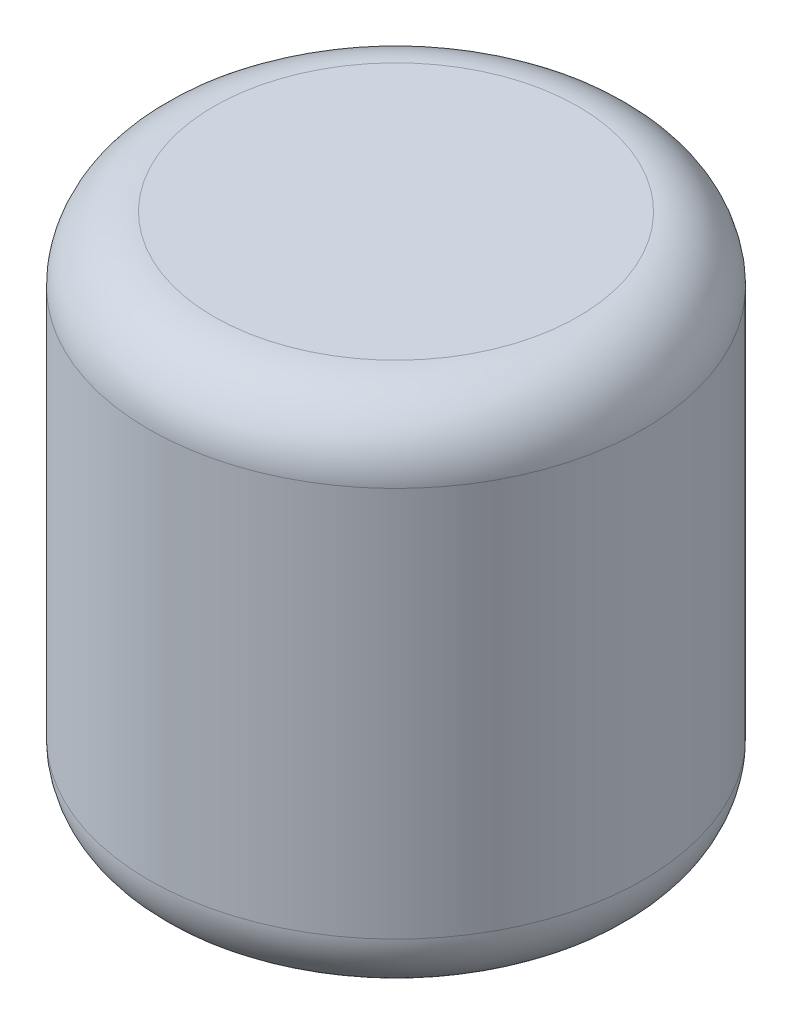
SolidWorks part; units mm, degrees
ref_plane "Front Plane" through (0, 0, 0) normal (0, 0, 1) x (1, 0, 0)
ref_plane "Top Plane" through (0, 0, 0) normal (0, 1, 0) x (1, 0, 0)
ref_plane "Right Plane" through (0, 0, 0) normal (1, 0, 0) x (0, 0, -1)
sketch "Sketch1" plane through (0, 0, 0) normal (0, 1, 0) x (1, 0, 0)
  circle A0 centre (0, 0) radius 1.9
  dimension "D1" = 3.8
extrude "Boss-Extrude1" add sketch "Sketch1" along normal blind 4
fillet "Fillet1" radius 0.5 2 edges at (0, 0, 1.9) (0, 4, 1.9)
